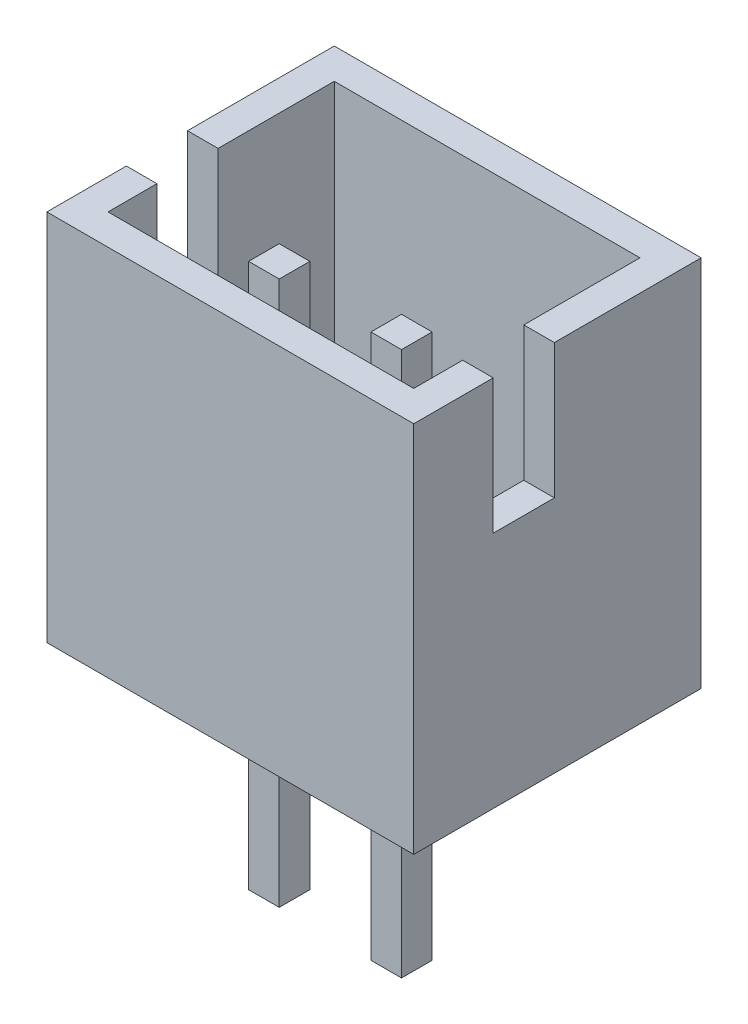
SolidWorks part; units mm, degrees
ref_plane "Front Plane" through (0, 0, 0) normal (0, 0, 1) x (1, 0, 0)
ref_plane "Top Plane" through (0, 0, 0) normal (0, 1, 0) x (1, 0, 0)
ref_plane "Right Plane" through (0, 0, 0) normal (1, 0, 0) x (0, 0, -1)
sketch "Sketch1" plane through (0, 0, 0) normal (0, 1, 0) x (1, 0, 0)
  line L1 (3, -2.35) -> (-3, -2.35)
  line L2 (3, -2.35) -> (3, 2.35)
  line L3 (3, 2.35) -> (-3, 2.35)
  line L4 (-3, -2.35) -> (-3, 2.35)
  line L5 (3, -2.35) -> (-3, 2.35) construction
  line L6 (3, 2.35) -> (-3, -2.35) construction
  point P0 (0, 0)
  dimension "D1" = 4.7
  dimension "D2" = 6
extrude "Boss-Extrude1" add sketch "Sketch1" along normal blind 6.1
shell "Shell1" thickness 0.5
sketch "Sketch2" plane through (0, 0.5, 0) normal (0, 1, 0) x (1, 0, 0)
  line L0 (-2.5, -0.55) -> (2.5, -0.55) construction
  line L1 (-2.5, 1.85) -> (-2.5, -1.85) construction
  line L2 (2.5, -1.85) -> (2.5, 1.85) construction
  line L4 (-3, -2.35) -> (3, -2.35) construction
  line L6 (-0.75, -0.8) -> (-1.25, -0.8)
  line L7 (-0.75, -0.8) -> (-0.75, -0.3)
  line L8 (-0.75, -0.3) -> (-1.25, -0.3)
  line L9 (-1.25, -0.8) -> (-1.25, -0.3)
  line L10 (-0.75, -0.8) -> (-1.25, -0.3) construction
  line L11 (-0.75, -0.3) -> (-1.25, -0.8) construction
  line L12 (0, -2.585) -> (0, 2.585) construction
  line L13 (0.75, -0.3) -> (1.25, -0.3)
  line L14 (1.25, -0.8) -> (1.25, -0.3)
  line L15 (0.75, -0.8) -> (1.25, -0.8)
  line L16 (0.75, -0.8) -> (0.75, -0.3)
  point P8 (-1, -0.55)
  dimension "D1" = 1.8
  dimension "D2" = 0.5
  dimension "D3" = 2
extrude "Boss-Extrude2" add sketch "Sketch2" along normal blind 5 and the other way blind 3.9 separate body
sketch "Sketch3" plane through (-3, 0, 0) normal (-1, 0, 0) x (0, 0, 1)
  line L0 (-2.35, 6.1) -> (2.35, 6.1) construction
  line L1 (1.05, 3.9) -> (0.05, 3.9)
  line L2 (1.05, 3.9) -> (1.05, 6.1)
  line L3 (1.05, 6.1) -> (0.05, 6.1)
  line L4 (0.05, 3.9) -> (0.05, 6.1)
  line L5 (1.05, 3.9) -> (0.05, 6.1) construction
  line L6 (1.05, 6.1) -> (0.05, 3.9) construction
  line L7 (-2.35, 0) -> (2.35, 0) construction
  line L9 (0.3, -3.4) -> (0.8, -3.4) construction
  point P0 (0.55, 5)
  point P14 (0.55, -3.4)
  dimension "D1" = 1
  dimension "D2" = 5
extrude "Cut-Extrude1" cut sketch "Sketch3" against normal up to surface (5.5 mm away)
mirror "Mirror1" about plane through (0, 0, 0) normal (1, 0, 0) of "Cut-Extrude1"
